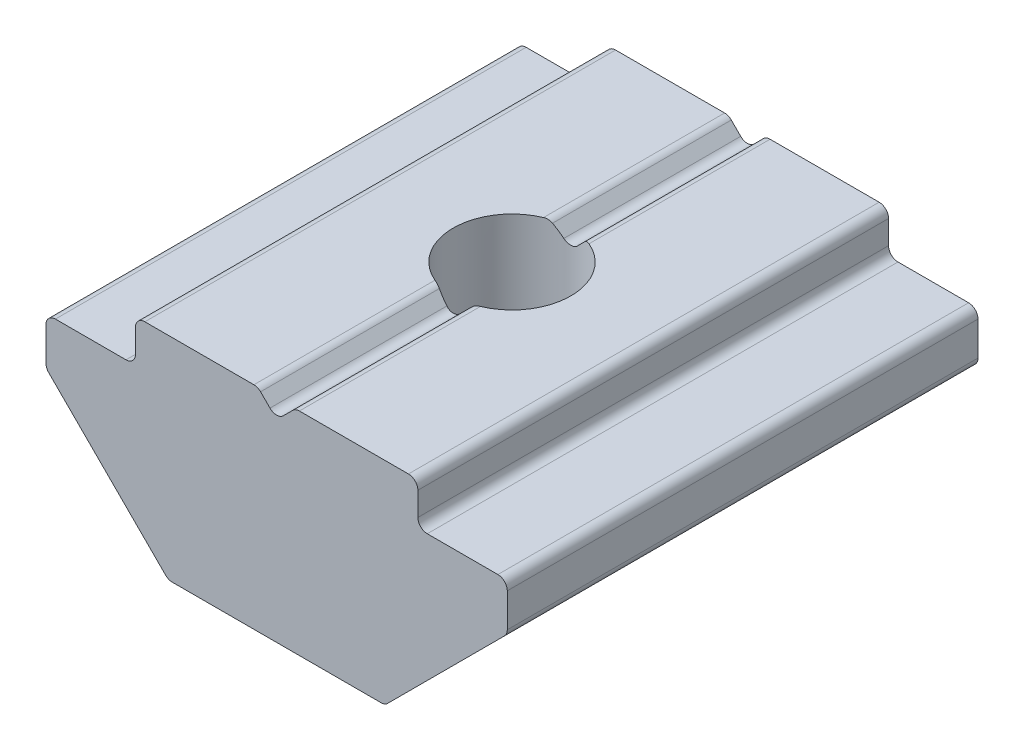
SolidWorks part; units mm, degrees
ref_plane "Front Plane" through (0, 0, 0) normal (0, 0, 1) x (1, 0, 0)
ref_plane "Top Plane" through (0, 0, 0) normal (0, 1, 0) x (1, 0, 0)
ref_plane "Right Plane" through (0, 0, 0) normal (1, 0, 0) x (0, 0, -1)
ref_plane "Plane1" through (0, 0, 5) normal (0, 0, 1) x (1, 0, 0)
sketch "Sketch1" plane through (0, 0, 5) normal (0, 0, 1) x (1, 0, 0)
  line L0 (4.9, -1) -> (4.9, 0.9)
  line L1 (4.9, 0.9) -> (-4.9, 0.9)
  line L2 (-4.9, 0.9) -> (-4.9, -1)
  line L3 (-4.9, -1) -> (-2.3, -3.6)
  line L4 (-2.3, -3.6) -> (2.3, -3.6)
  line L5 (2.3, -3.6) -> (4.9, -1)
  point P7 (4.9, -1.9517)
  dimension "D1" = 4.5
  dimension "D2" = 9.8
  dimension "D3" = 1.9
  dimension "D4" = 4.6
  dimension "D5" = 4.9
  dimension "D6" = 0.9
  dimension "D7" = 2.3
  dimension "D8" = 4.5
extrude "Boss-Extrude1" add sketch "Sketch1" against normal blind 10
sketch "Sketch2" plane through (0, 0, -5) normal (0, 0, -1) x (-1, 0, 0)
  line L0 (4.9, 0.9) -> (3, 0.9)
  line L1 (3, 0.9) -> (3, 0)
  line L2 (3, 0) -> (4.9, 0)
  line L3 (4.9, 0) -> (4.9, 0.9)
extrude "Cut-Extrude1" cut sketch "Sketch2" against normal through all
sketch "Sketch3" plane through (0, 0, -5) normal (0, 0, -1) x (-1, 0, 0)
  line L0 (-4.9, 0) -> (-3, 0)
  line L1 (-3, 0) -> (-3, 0.9)
  line L2 (-3, 0.9) -> (-4.9, 0.9)
  line L3 (-4.9, 0.9) -> (-4.9, 0)
extrude "Cut-Extrude2" cut sketch "Sketch3" against normal through all
sketch "Sketch4" plane through (0, 0, -5) normal (0, 0, -1) x (-1, 0, 0)
  line L0 (0.4, 0.9) -> (-0.4, 0.9)
  line L1 (-0.4, 0.9) -> (0, 0.5)
  line L2 (0, 0.5) -> (0.4, 0.9)
extrude "Cut-Extrude3" cut sketch "Sketch4" against normal through all
hole_wizard "Ø4.2 (4.2) Diameter Hole1" positions "Sketch6" profile "Sketch5" hole size "Ø4.2" standard "ANSI Metric"
sketch "Sketch6" plane through (0, -3.6, 0) normal (0, -1, 0) x (-1, 0, 0)
  point P0 (0, 0)
sketch "Sketch5" plane through (0, -3.6, 0) normal (1, 0, 0) x (0, 0, -1)
  line L0 (0, 0) -> (0, 4.5)
  line L1 (0, 4.5) -> (1.25, 4.5)
  line L2 (1.25, 4.5) -> (1.25, 0)
  line L5 (1.25, 0) -> (0, 0)
  line L11 (0, -6.35) -> (0, 107.95) construction
  dimension "Thru Hole Dia." = 2.5
  dimension "Thru Hole Depth" = 4.5
fillet "Fillet1" radius 0.2 16 edges at (4.9, 0, 0) (3, 0, 0) (-4.9, -1, 0) (3, 0.9, 0) (-3, 0, 0) (0.4, 0.9, -3.0921) (0, 0.5, 3.125) (-0.4, 0.9, -3.0921) (4.9, -1, 0) (-3, 0.9, 0) (0, 0.5, -3.125) (-0.4, 0.9, 3.0921) (-4.9, 0, 0) (-2.3, -3.6, 0) (0.4, 0.9, 3.0921) (2.3, -3.6, 0)
